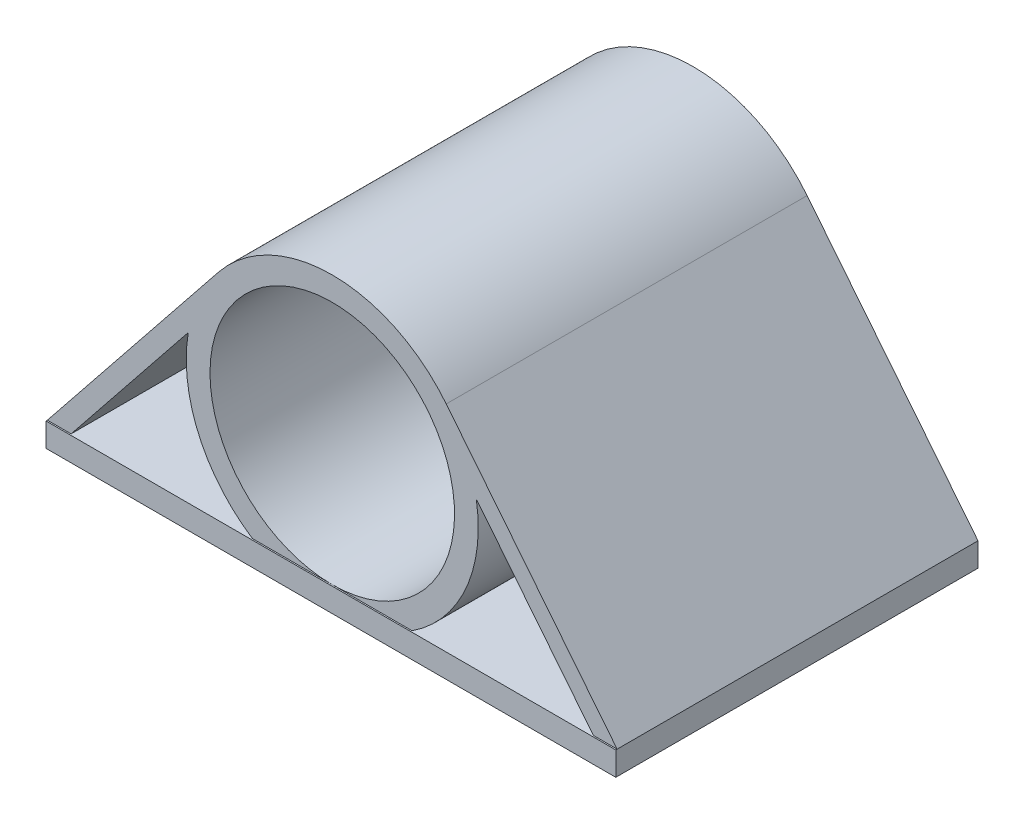
SolidWorks part; units mm, degrees
ref_plane "Front Plane" through (0, 0, 0) normal (0, 0, 1) x (1, 0, 0)
ref_plane "Top Plane" through (0, 0, 0) normal (0, 1, 0) x (1, 0, 0)
ref_plane "Right Plane" through (0, 0, 0) normal (1, 0, 0) x (0, 0, -1)
sketch "Sketch1" plane through (0, 0, 0) normal (0, 0, 1) x (1, 0, 0)
  circle A0 centre (0, 0) radius 30.75
  circle A1 centre (0, 0) radius 25.75
  dimension "D1" = 51.5
  dimension "D2" = 61.5
extrude "Boss-Extrude2" add sketch "Sketch1" along normal blind 76
sketch "Sketch2" plane through (0, 0, 0) normal (0, 0, -1) x (-1, 0, 0)
  circle A0 centre (0, 0) radius 25.75
  dimension "D1" = 51.5
extrude "Boss-Extrude3" add sketch "Sketch2" against normal blind 5
sketch "Sketch3" plane through (0, 0, 0) normal (0, 0, -1) x (-1, 0, 0)
  circle A0 centre (0, 0) radius 10.75
  dimension "D1" = 21.5
extrude "Cut-Extrude1" cut sketch "Sketch3" against normal blind 5 contours A0
sketch "Sketch8" plane through (0, 0, 0) normal (0, 0, -1) x (-1, 0, 0)
  line L0 (0, 30.75) -> (0, -30.75) construction
  circle A0 centre (0, 0) radius 30.75 construction
  circle A1 centre (20, 0) radius 2.75
  circle A2 centre (-20, 0) radius 2.75
  dimension "D1" = 5.5
  dimension "D2" = 20
extrude "Cut-Extrude3" cut sketch "Sketch8" against normal blind 5
ref_plane "Plane1" through (0, -30.75, 0) normal (0, 1, 0) x (1, 0, 0)
sketch "Sketch9" plane through (0, -30.75, 0) normal (0, 1, 0) x (1, 0, 0)
  line L0 (60, 0) -> (-60, 0)
  line L1 (-60, -76.2883) -> (60, -76.2883)
  line L2 (60, -76.2883) -> (60, 0)
  line L3 (-60, 0) -> (-60, -76.2883)
  point P4 (0, 0)
  point P8 (0, -76.2883)
extrude "Boss-Extrude4" add sketch "Sketch9" along normal blind 5
sketch "Sketch11" plane through (0, 0, 76) normal (0, 0, 1) x (1, 0, 0)
  line L0 (-60, -25.75) -> (-24.0063, 19.2161)
  line L1 (-60, -25.75) -> (-55, -25.75)
  line L2 (-55, -25.75) -> (-30.329, 5.0709)
  line L4 (55, -25.75) -> (30.329, 5.0709)
  line L5 (60, -25.75) -> (55, -25.75)
  line L6 (60, -25.75) -> (24.0063, 19.2161)
  line L7 (-24.0063, 19.2161) -> (-30.329, 5.0709)
  line L8 (24.0063, 19.2161) -> (30.329, 5.0709)
  arc A0 (16.8077, -25.75) -> (-16.8077, -25.75) centre (0, 0) ccw construction
extrude "Boss-Extrude5" add sketch "Sketch11" against normal through all
